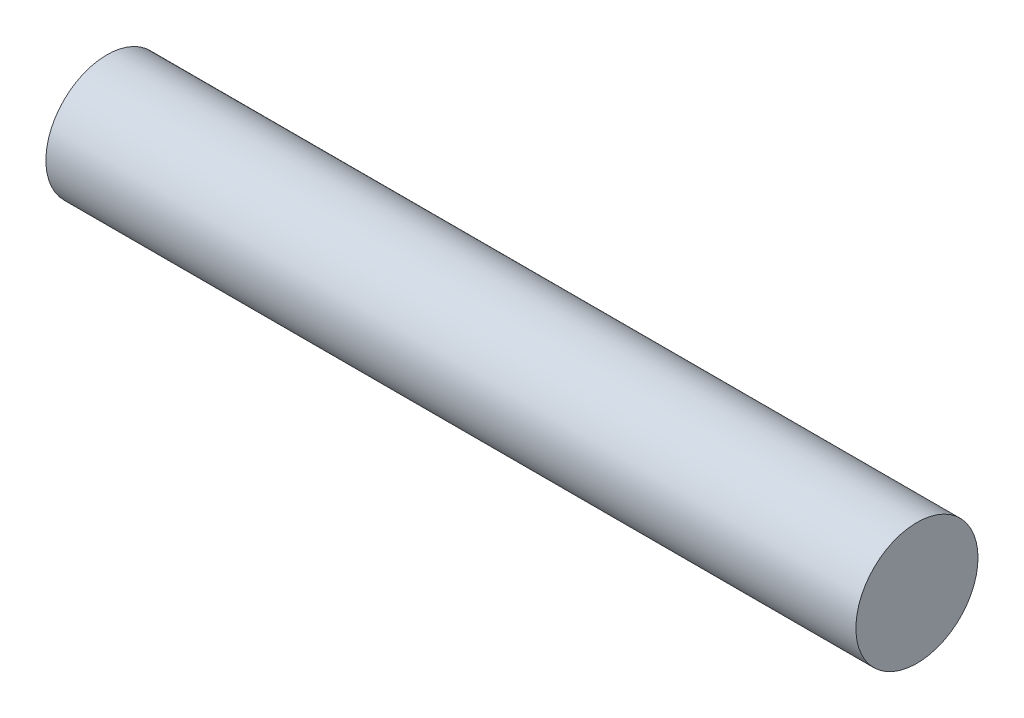
SolidWorks part; units mm, degrees
material "1060 Alloy"
ref_plane "Front Plane" through (0, 0, 0) normal (0, 0, 1) x (1, 0, 0)
ref_plane "Top Plane" through (0, 0, 0) normal (0, 1, 0) x (1, 0, 0)
ref_plane "Right Plane" through (0, 0, 0) normal (1, 0, 0) x (0, 0, -1)
sketch "Croquis1" plane through (0, 0, 0) normal (0, 0, 1) x (1, 0, 0)
  line L0 (9.95, 0) -> (-9.95, 0) construction
  line L1 (-9.95, 0) -> (-9.95, 1.5)
  line L2 (-9.95, 1.5) -> (9.95, 1.5)
  line L3 (9.95, 1.5) -> (9.95, 0)
  line L4 (-9.95, 0) -> (9.95, 0)
  point P4 (0, 0)
  dimension "D1" = 19.9
  dimension "D2" = 3
revolve "Revolución1" add sketch "Croquis1" angle 360 about L0
